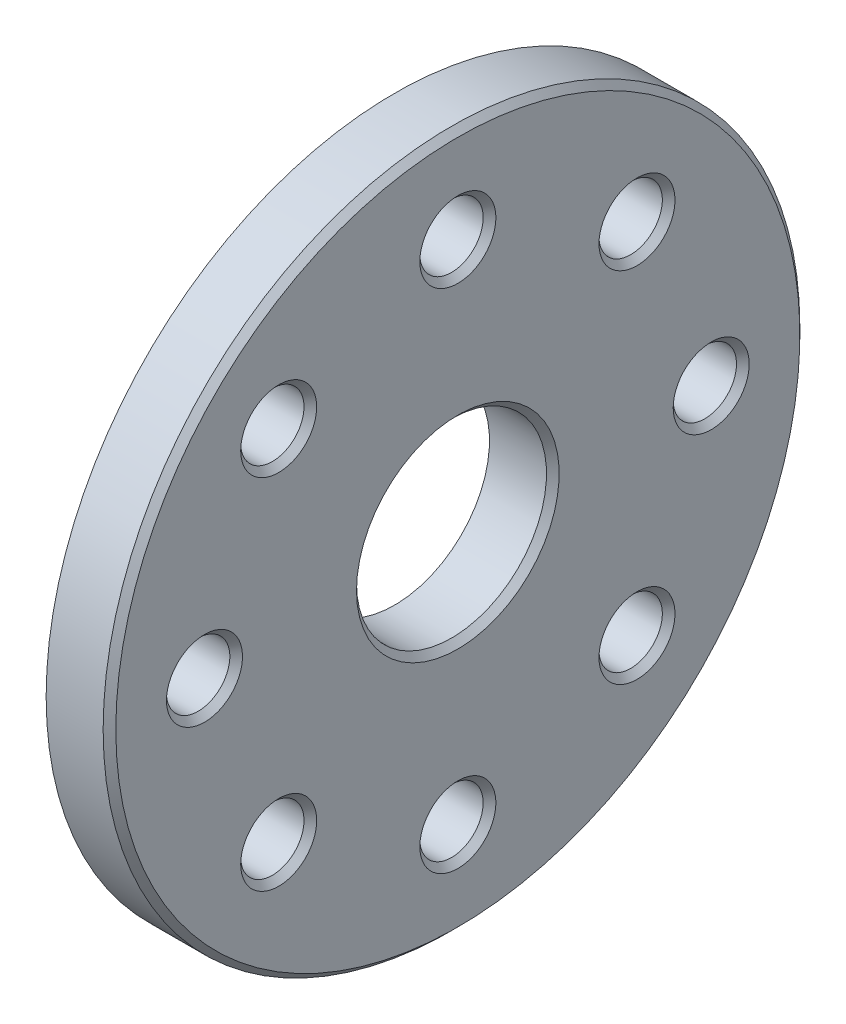
SolidWorks part; units mm, degrees
ref_plane "Ön Düzlem" through (0, 0, 0) normal (0, 0, 1) x (1, 0, 0)
ref_plane "Üst Düzlem" through (0, 0, 0) normal (0, 1, 0) x (1, 0, 0)
ref_plane "Sağ Düzlem" through (0, 0, 0) normal (1, 0, 0) x (0, 0, -1)
sketch "Sketch2" plane through (0, 0, 0) normal (0, 0, 1) x (1, 0, 0)
  line L0 (-1, 3) -> (-1, 11)
  line L1 (-1, 11) -> (1, 11)
  line L2 (1, 11) -> (1, 3)
  line L3 (1, 3) -> (-1, 3)
  line L4 (0, 0) -> (0, 3) construction
  line L5 (0, 0) -> (3.766, 0) construction
  dimension "D1" = 3
  dimension "D2" = 11
  dimension "D3" = 2
revolve "Revolve1" add sketch "Sketch2" angle 360 about L5
sketch "Sketch3" plane through (-1, 0, 0) normal (-1, 0, 0) x (0, 0, 1)
  circle A0 centre (0, 8) radius 1
  dimension "D1" = 2
  dimension "D2" = 8
extrude "Cut-Extrude1" cut sketch "Sketch3" against normal through all
pattern_circular "CirPattern1" count 8 over 360 about axis through (0, 0, 0) along (1, 0, 0) of "Cut-Extrude1"
chamfer "Chamfer1" distance 0.2 angle 45 10 edges at (1, 0, 3) (1, 0, 11) (1, 8, 1) (1, 6.364, -4.9497) (1, 1, -8) (1, -4.9497, -6.364) (1, -8, -1) (1, -6.364, 4.9497) (1, -1, 8) (1, 4.9497, 6.364)
